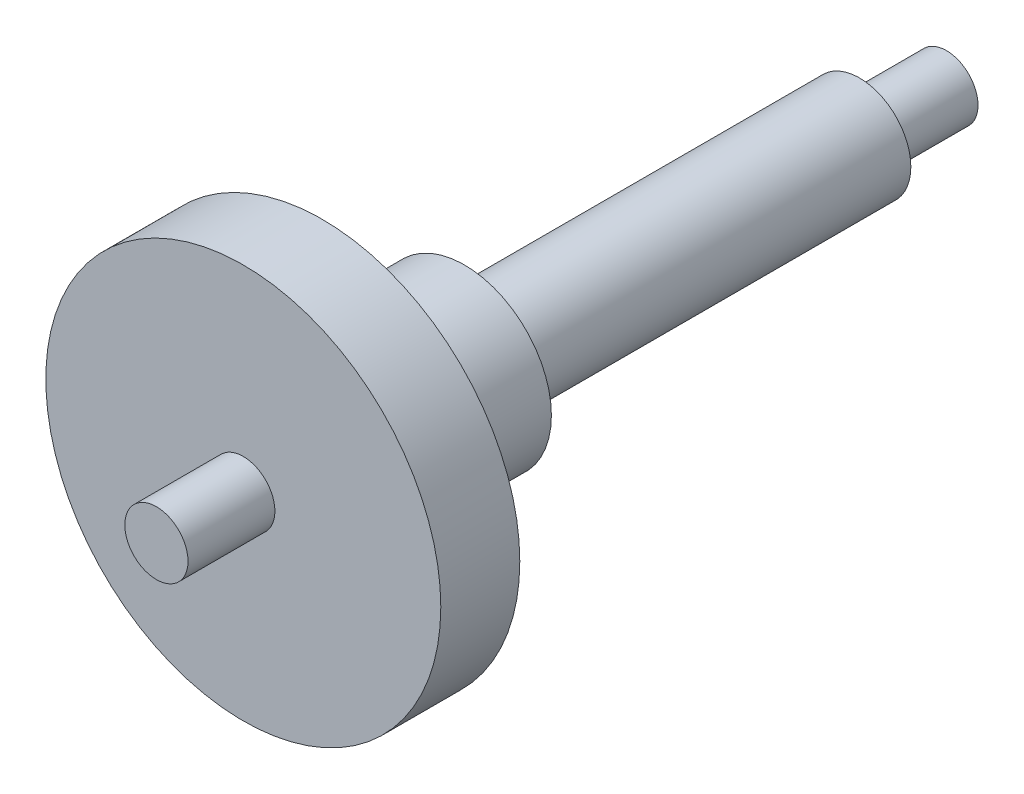
SolidWorks part; units mm, degrees
ref_plane "Front" through (0, 0, 0) normal (0, 0, 1) x (1, 0, 0)
ref_plane "Top" through (0, 0, 0) normal (0, 1, 0) x (1, 0, 0)
ref_plane "Right" through (0, 0, 0) normal (1, 0, 0) x (0, 0, -1)
sketch "Sketch1" plane through (0, 0, 0) normal (0, 0, 1) x (1, 0, 0)
  circle A0 centre (0, 0) radius 0.4
  dimension "D1" = 0.8
extrude "Boss-Extrude1" add sketch "Sketch1" along normal blind 1.1
sketch "Sketch2" plane through (0, 0, 1.1) normal (0, 0, 1) x (1, 0, 0)
  circle A0 centre (0, 0) radius 0.65
  dimension "D1" = 1.3
extrude "Boss-Extrude2" add sketch "Sketch2" along normal blind 5
sketch "Sketch3" plane through (0, 0, 6.1) normal (0, 0, 1) x (1, 0, 0)
  circle A0 centre (0, 0) radius 1.1
  dimension "D1" = 2.2
extrude "Boss-Extrude3" add sketch "Sketch3" along normal blind 1.8
sketch "Sketch4" plane through (0, 0, 7.9) normal (0, 0, 1) x (1, 0, 0)
  circle A0 centre (0, 0) radius 2.5
  dimension "D1" = 5
extrude "Boss-Extrude4" add sketch "Sketch4" along normal blind 1
sketch "Sketch5" plane through (0, 0, 8.9) normal (0, 0, 1) x (1, 0, 0)
  circle A0 centre (0, 0) radius 0.4
  dimension "D1" = 0.8
extrude "Boss-Extrude5" add sketch "Sketch5" along normal blind 1.1
